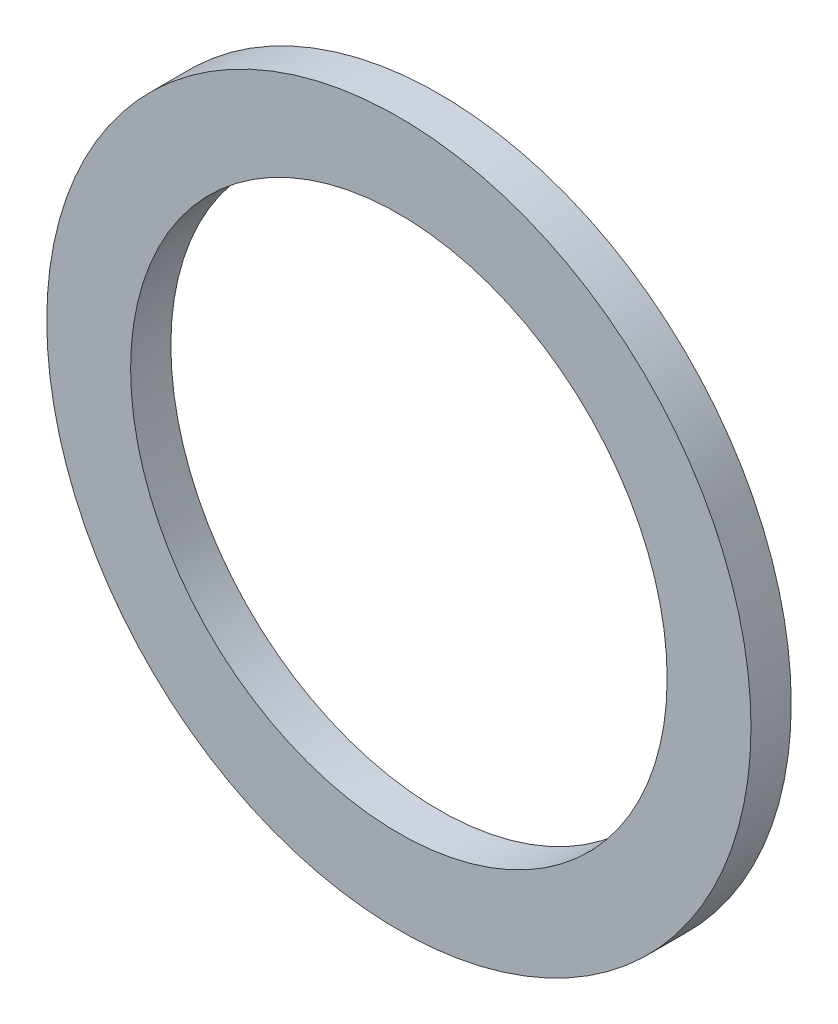
SolidWorks part; units mm, degrees
ref_plane "前视基准面" through (0, 0, 0) normal (0, 0, 1) x (1, 0, 0)
ref_plane "上视基准面" through (0, 0, 0) normal (0, 1, 0) x (1, 0, 0)
ref_plane "右视基准面" through (0, 0, 0) normal (1, 0, 0) x (0, 0, -1)
sketch "草图1" plane through (0, 0, 0) normal (0, 0, 1) x (1, 0, 0)
  circle A0 centre (0, 0) radius 40
  circle A1 centre (0, 0) radius 52.5
  dimension "D1" = 80
  dimension "D2" = 105
extrude "凸台-拉伸1" add sketch "草图1" along normal blind 6
